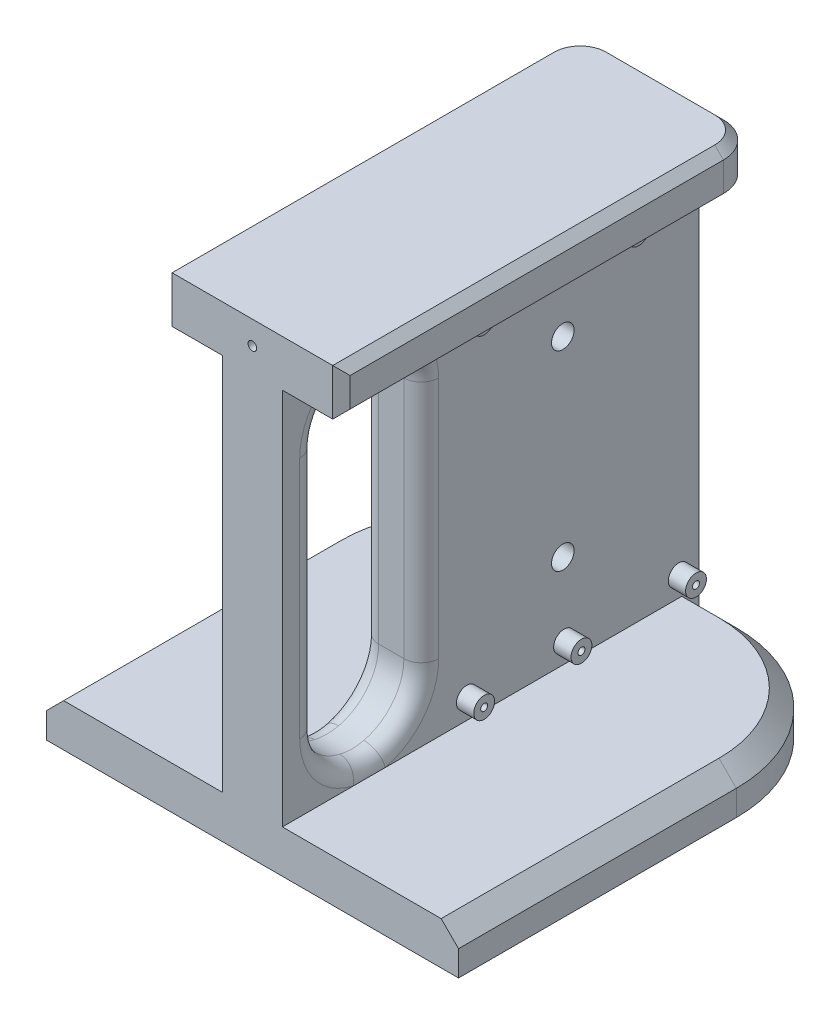
SolidWorks part; units mm, degrees
ref_plane "Front Plane" through (0, 0, 0) normal (0, 0, 1) x (1, 0, 0)
ref_plane "Top Plane" through (0, 0, 0) normal (0, 1, 0) x (1, 0, 0)
ref_plane "Right Plane" through (0, 0, 0) normal (1, 0, 0) x (0, 0, -1)
sketch "Sketch2" plane through (0, 0, 0) normal (0, 0, 1) x (1, 0, 0)
  line L1 (8.6309, 54.4617) -> (-8.6309, 54.4617)
  line L2 (8.6309, 54.4617) -> (8.6309, -54.4617)
  line L3 (8.6309, -54.4617) -> (-8.6309, -54.4617)
  line L4 (-8.6309, 54.4617) -> (-8.6309, -54.4617)
  line L5 (8.6309, 54.4617) -> (-8.6309, -54.4617) construction
  line L6 (8.6309, -54.4617) -> (-8.6309, 54.4617) construction
  line L7 (25.6251, 67.8429) -> (-25.6251, 67.8429)
  line L8 (25.6251, 67.8429) -> (25.6251, 54.4617)
  line L9 (25.6251, 54.4617) -> (-25.6251, 54.4617)
  line L10 (-25.6251, 67.8429) -> (-25.6251, 54.4617)
  line L11 (25.6251, 67.8429) -> (-25.6251, 54.4617) construction
  line L12 (25.6251, 54.4617) -> (-25.6251, 67.8429) construction
  line L13 (-59.3458, -66.7724) -> (59.3458, -66.7724)
  line L14 (-59.3458, -66.7724) -> (-59.3458, -54.4617)
  line L15 (-59.3458, -54.4617) -> (59.3458, -54.4617)
  line L16 (59.3458, -66.7724) -> (59.3458, -54.4617)
  line L17 (-59.3458, -66.7724) -> (59.3458, -54.4617) construction
  line L18 (-59.3458, -54.4617) -> (59.3458, -66.7724) construction
  point P0 (0, 0)
  point P6 (0, 61.1523)
  point P11 (0, -60.617)
extrude "Boss-Extrude1" add sketch "Sketch2" along normal blind 60 and the other way blind 60 contours L7 L10 L9 L1 L8 | L1 L4 L3 L2 | L13 L16 L15 L3 L14
sketch "Sketch3" plane through (8.6309, 0, 0) normal (1, 0, 0) x (0, 0, -1)
  line L0 (22.75, 52.1393) -> (22.75, -52.1328) construction
  line L1 (-60, 54.4617) -> (60, 54.4617)
  line L2 (-60, 54.4617) -> (-60, -54.4617)
  line L3 (-60, -54.4617) -> (60, -54.4617)
  line L4 (60, 54.4617) -> (60, -54.4617)
  line L5 (-60, 54.4617) -> (60, -54.4617) construction
  line L6 (-60, -54.4617) -> (60, 54.4617) construction
  line L7 (59, 51.8672) -> (-13.5, 51.8672)
  line L8 (59, 51.8672) -> (59, -52.1328)
  line L9 (59, -52.1328) -> (-13.5, -52.1328)
  line L10 (-13.5, 51.8672) -> (-13.5, -52.1328)
  line L11 (22.75, -52.1328) -> (22.75, 0.0032) construction
  line L12 (-13.5, 0.1393) -> (59, -0.1328) construction
  line L13 (-13.5, -48.6911) -> (59, -48.6911) construction
  line L14 (-6.9, -51.6381) -> (-6.9, 51.8672) construction
  line L15 (-13.5, 47.1687) -> (59, 47.1687) construction
  circle A0 centre (-6.9, -48.6911) radius 1
  circle A1 centre (21.1, -48.6911) radius 1
  circle A2 centre (54.1, -48.6911) radius 1
  circle A3 centre (-6.9, 47.1687) radius 1
  circle A4 centre (37.6, 47.1687) radius 1
  circle A5 centre (54.1, 48.8187) radius 1
  circle A6 centre (-6.9, 47.1687) radius 3
  circle A7 centre (37.6, 47.1687) radius 3
  circle A8 centre (54.1, 48.8187) radius 3
  circle A9 centre (-6.9, -48.6911) radius 3
  circle A10 centre (21.1, -48.6911) radius 3
  circle A11 centre (54.1, -48.6911) radius 3
  point P0 (0, 0)
  point P14 (22.75, 0.0032)
  point P18 (22.75, 0.0032)
  point P29 (-6.9, 0.1145)
  point P34 (22.75, 47.1687)
  dimension "D4" = 2
  dimension "D5" = 2
  dimension "D6" = 2
  dimension "D12" = 2
  dimension "D13" = 2
  dimension "D14" = 2
  dimension "D17" = 6
  dimension "D18" = 6
  dimension "D19" = 6
  dimension "D20" = 6
  dimension "D21" = 6
  dimension "D22" = 6
  dimension "D1" = 72.5
  dimension "D2" = 104
  dimension "D3" = 108.9233
  dimension "D7" = 28
  dimension "D8" = 33
  dimension "D9" = 6.6
  dimension "D10" = 44.5
  dimension "D11" = 1.65
  dimension "D15" = 16.5
  dimension "D16" = 1
extrude "Boss-Extrude2" add sketch "Sketch3" along normal blind 5 contours A6 A3 | A7 A4 | A8 A5 | A11 A2 | A10 A1 | A9 A0
sketch "Sketch4" plane through (8.6309, 0, 0) normal (1, 0, 0) x (0, 0, -1)
  line L0 (11.6386, 24.2117) -> (29.8614, 24.2117) construction
  line L1 (12.5337, -24.2883) -> (28.9663, -24.2883) construction
  line L4 (20.75, 24.2117) -> (20.75, -24.2883) construction
  line L5 (60, 54.4617) -> (-60, 54.4617) construction
  line L7 (60, 54.4617) -> (60, -54.4617) construction
  line L8 (-8.5, 33.7117) -> (50, 33.7117) construction
  line L9 (-8.5, 33.7117) -> (-8.5, -33.7883) construction
  line L10 (-8.5, -33.7883) -> (50, -33.7883) construction
  line L11 (50, 33.7117) -> (50, -33.7883) construction
  line L12 (-8.5, 33.7117) -> (50, -33.7883) construction
  line L13 (-8.5, -33.7883) -> (50, 33.7117) construction
  circle A0 centre (20.75, 27.4617) radius 3.25
  circle A1 centre (20.75, -27.5383) radius 3.25
  point P4 (20.75, -0.0383)
  point P7 (20.75, 24.2117)
  point P10 (20.75, -24.2883)
  point P13 (20.75, -0.0383)
  dimension "D1" = 48.5
  dimension "D3" = 6.5
  dimension "D4" = 6.5
  dimension "D2" = 54.5
  dimension "D5" = 67.5
  dimension "D6" = 58.5
  dimension "D7" = 10
extrude "Cut-Extrude1" cut sketch "Sketch4" against normal mid plane 42 from offset 0
sketch "Sketch5" plane through (8.6309, 0, 0) normal (1, 0, 0) x (0, 0, -1)
  line L0 (-35, 35) -> (-35, -35) construction
  line L1 (-20, 35) -> (-20, -35)
  line L2 (-50, 35) -> (-50, -35)
  line L3 (-60, 0) -> (60, 0) construction
  line L4 (60, 54.4617) -> (60, -54.4617) construction
  line L5 (-60, 54.4617) -> (-60, -54.4617) construction
  arc A0 (-20, 35) -> (-50, 35) centre (-35, 35) ccw
  arc A1 (-50, -35) -> (-20, -35) centre (-35, -35) ccw
  point P2 (-35, 0)
  point P13 (0, 0)
  dimension "D1" = 0
  dimension "D2" = 30
  dimension "D3" = 70
  dimension "D4" = 25
extrude "Cut-Extrude2" cut sketch "Sketch5" against normal through all contours L2 A1 L1 A0
fillet "Fillet1" radius 40 2 edges at (-59.3458, -60.617, -60) (59.3458, -60.617, -60)
fillet "Fillet3" radius 5 8 edges at (8.6309, 50, 35) (8.6309, 0, 50) (8.6309, -50, 35) (-8.6309, -50, 35) (-8.6309, 0, 50) (-8.6309, 50, 35) (8.6309, 0, 20) (-8.6309, 0, 20)
fillet "Fillet4" radius 10 2 edges at (-25.6251, 61.1523, -60) (25.6251, 61.1523, -60)
sketch "Sketch6" plane through (0, 0, -60) normal (0, 0, -1) x (-1, 0, 0)
  line L0 (0, 0) -> (0, -50000) construction
  line L1 (-15.6251, 67.8429) -> (15.6251, 67.8429) construction
  circle A0 centre (11.75, 61.3429) radius 1
  circle A1 centre (-11.75, 61.3429) radius 1
  point P9 (0, 0)
  dimension "D3" = 2
  dimension "D4" = 2
  dimension "D1" = 23.5
  dimension "D2" = 11.75
  dimension "D5" = 6.5
  dimension "D6" = 6.5
extrude "Cut-Extrude3" cut sketch "Sketch6" against normal blind 7.5
chamfer "Chamfer2" distance 2.5 angle 45 13 edges at (-25.6251, 67.8429, 5) (-22.6962, 67.8429, -57.0711) (0, 67.8429, -60) (12.128, 54.4617, -60) (22.6962, 67.8429, -57.0711) (22.6962, 54.4617, -57.0711) (25.6251, 67.8429, 5) (25.6251, 61.1523, 60) (25.6251, 54.4617, 5) (-12.128, 54.4617, -60) (-22.6962, 54.4617, -57.0711) (-25.6251, 54.4617, 5) (-25.6251, 61.1523, 60)
chamfer "Chamfer4" distance 5 angle 45 6 edges at (13.9884, -54.4617, -60) (47.6301, -54.4617, -48.2843) (59.3458, -54.4617, 20) (-13.9884, -54.4617, -60) (-59.3458, -54.4617, 20) (-47.6301, -54.4617, -48.2843)
sketch "Sketch7" plane through (0, 0, 60) normal (0, 0, 1) x (1, 0, 0)
  line L0 (-23.1251, 61.1523) -> (49976.8749, 61.1523) construction
  line L1 (-23.1251, 67.8429) -> (-23.1251, 54.4617) construction
  line L2 (0, 0) -> (0, -50000) construction
  circle A0 centre (0, 61.1523) radius 1.25
  point P4 (-23.1251, 61.1523)
  dimension "D1" = 2.5
extrude "Cut-Extrude4" cut sketch "Sketch7" against normal blind 7.5
